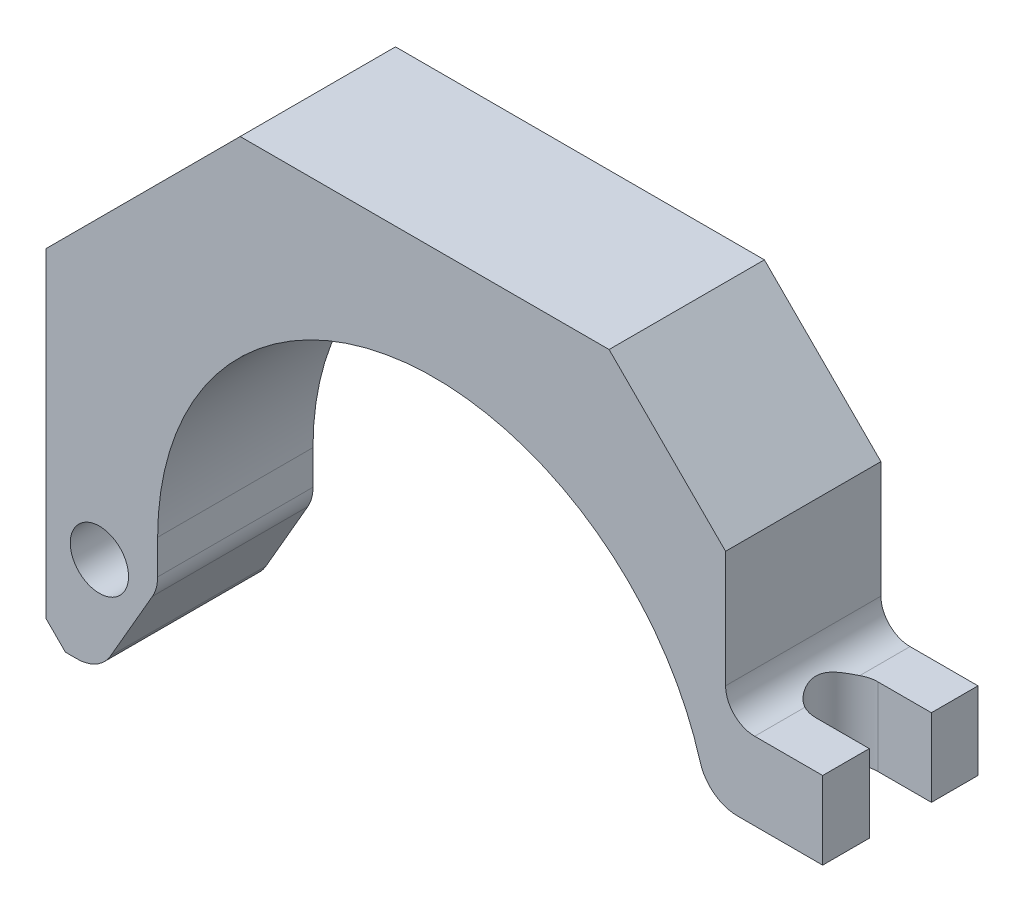
SolidWorks part; units mm, degrees
ref_plane "前视基准面" through (0, 0, 0) normal (0, 0, 1) x (1, 0, 0)
ref_plane "上视基准面" through (0, 0, 0) normal (0, 1, 0) x (1, 0, 0)
ref_plane "右视基准面" through (0, 0, 0) normal (1, 0, 0) x (0, 0, -1)
sketch "草图1" plane through (0, 0, 0) normal (0, 0, 1) x (1, 0, 0)
  line L0 (0, 20) -> (0, -20) construction
  line L1 (-40, 20) -> (40, 20)
  line L2 (-40, 20) -> (-40, -20)
  line L4 (40, 20) -> (40, -20)
  line L5 (-40, 20) -> (40, -20) construction
  line L6 (-40, -20) -> (40, 20) construction
  line L7 (28.5, -20) -> (40, -20)
  line L8 (-40, -20) -> (-40, -35)
  line L9 (-40, -35) -> (-28.5, -35)
  line L10 (-28.5, -35) -> (-28.5, -20)
  arc A0 (28.5, -20) -> (-28.5, -20) centre (0, -20) ccw
  circle A1 centre (-34.5, -25) radius 3
  point P0 (0, 0)
  dimension "D3" = 57
  dimension "D5" = 6
  dimension "D6" = 5.5
  dimension "D7" = 45
  dimension "D1" = 80
  dimension "D2" = 40
  dimension "D4" = 15
extrude "凸台-拉伸1" add sketch "草图1" along normal blind 16
chamfer "倒角1" distance 6 angle 60 1 edges at (-28.5, -35, 8)
sketch "草图2" plane through (0, 0, 16) normal (0, 0, 1) x (1, 0, 0)
  line L0 (28.5, -20) -> (40, -20) construction
  line L1 (-17.5121, -15) -> (52.6886, -15)
  line L2 (-17.5121, -15) -> (-17.5121, -26.3693)
  line L3 (-17.5121, -26.3693) -> (52.6886, -26.3693)
  line L4 (52.6886, -15) -> (52.6886, -26.3693)
  line L5 (-17.5121, -15) -> (52.6886, -26.3693) construction
  line L6 (-17.5121, -26.3693) -> (52.6886, -15) construction
  point P0 (17.5883, -20.6846)
  dimension "D1" = 5
extrude "切除-拉伸1" cut sketch "草图2" against normal through all
chamfer "倒角2" distance 20 angle 45 1 edges at (-40, 20, 8)
sketch "草图4" plane through (0, 0, 16) normal (0, 0, 1) x (1, 0, 0)
  line L0 (40, -15) -> (28.058, -15) construction
  line L1 (30, 22.6404) -> (45.0649, 22.6404)
  line L2 (30, 22.6404) -> (30, -7)
  line L3 (30, -7) -> (45.0649, -7)
  line L4 (45.0649, 22.6404) -> (45.0649, -7)
  line L5 (40, -15) -> (40, 20) construction
  dimension "D1" = 8
  dimension "D2" = 10
extrude "切除-拉伸2" cut sketch "草图4" against normal through all
chamfer "倒角3" distance 12 angle 45 1 edges at (30, 20, 8)
fillet "圆角1" radius 3 1 edges at (30, -7, 8)
fillet "圆角2" radius 4 1 edges at (-28.5, -24.6077, 8)
fillet "圆角3" radius 4 1 edges at (-34.5, -35, 8)
fillet "圆角4" radius 4 1 edges at (28.058, -15, 8)
chamfer "倒角4" distance 2 angle 45 1 edges at (-40, -35, 8)
sketch "草图5" plane through (0, -15, 0) normal (0, -1, 0) x (1, 0, 0)
  line L0 (34.5, 8) -> (41.1782, 8) construction
  line L1 (34.5, 11.2) -> (41.1782, 11.2)
  line L2 (34.5, 4.8) -> (41.1782, 4.8)
  line L3 (40, 16) -> (40, 0) construction
  arc A0 (34.5, 11.2) -> (34.5, 4.8) centre (34.5, 8) ccw
  arc A1 (41.1782, 4.8) -> (41.1782, 11.2) centre (41.1782, 8) ccw
  point P2 (37.8391, 8)
  dimension "D1" = 3.2
  dimension "D2" = 5.5
extrude "切除-拉伸3" cut sketch "草图5" against normal blind 10
